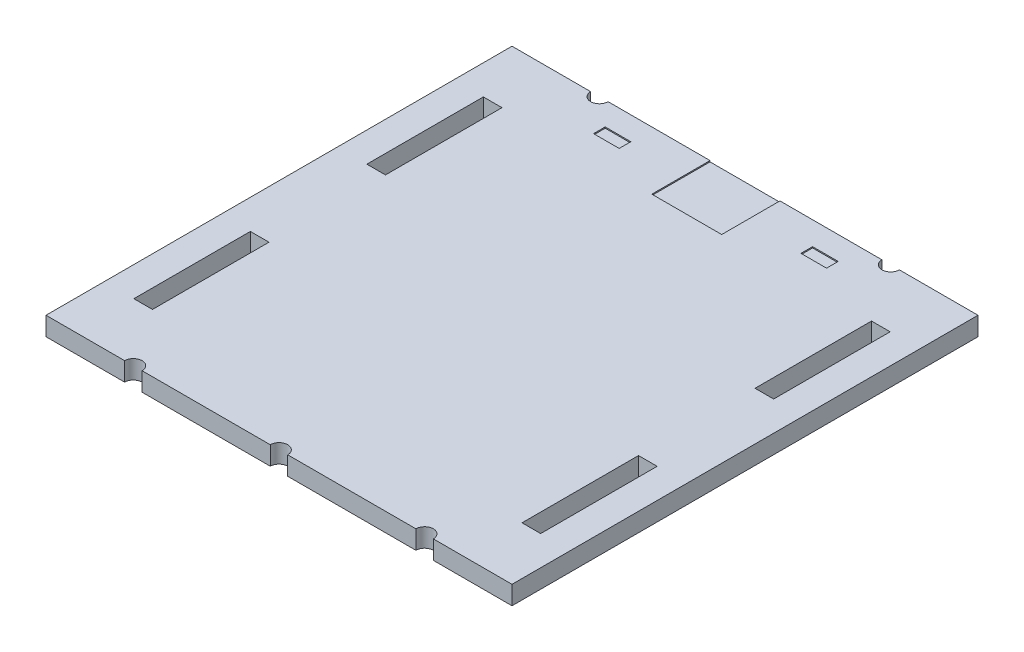
SolidWorks part; units mm, degrees
ref_plane "정면" through (0, 0, 0) normal (0, 0, 1) x (1, 0, 0)
ref_plane "윗면" through (0, 0, 0) normal (0, 1, 0) x (1, 0, 0)
ref_plane "우측면" through (0, 0, 0) normal (1, 0, 0) x (0, 0, -1)
sketch "스케치1" plane through (0, 0, 0) normal (0, 1, 0) x (1, 0, 0)
  line L1 (0, 0) -> (40, 0)
  line L2 (0, 0) -> (0, 40)
  line L3 (0, 40) -> (40, 40)
  line L4 (40, 0) -> (40, 40)
  dimension "D1" = 40
  dimension "D2" = 40
extrude "보스-돌출1" add sketch "스케치1" along normal blind 1.6
sketch "스케치2" plane through (0, 1.6, 0) normal (0, 1, 0) x (1, 0, 0)
  line L0 (0, 0) -> (40, 0) construction
  line L1 (40, 40) -> (0, 40) construction
  line L2 (0, 40) -> (0, 0) construction
  line L3 (40, 0) -> (40, 40) construction
  point P0 (7.5, 0)
  point P1 (20, 0)
  point P4 (32.5, 0)
  point P5 (32.5, 40)
  point P6 (20, 40)
  point P9 (7.5, 40)
  dimension "D1" = 7.5
  dimension "D2" = 7.5
hole_wizard "Ø1.5 (1.5) 지름 구멍1" positions "스케치5" profile "스케치6" hole size "Ø1.5" standard "ISO" end condition through all
sketch "스케치5" plane through (0, 1.6, 0) normal (0, 1, 0) x (1, 0, 0)
  point P0 (7.5, 0)
  point P3 (7.5, 40)
  point P6 (20, 0)
  point P9 (32.5, 0)
  point P12 (32.5, 40)
sketch "스케치6" plane through (7.5, 1.6, 0) normal (1, 0, 0) x (0, 0, 1)
  line L0 (0, 0) -> (0, 1.6)
  line L1 (0, 1.6) -> (0.75, 1.6)
  line L2 (0.75, 1.6) -> (0.75, 0)
  line L5 (0.75, 0) -> (0, 0)
  line L11 (0, -6.35) -> (0, 107.95) construction
  dimension "관통 구멍 지름" = 1.5
  dimension "관통 구멍 깊이" = 1.6
sketch "스케치8" plane through (0, 1.6, 0) normal (0, 1, 0) x (1, 0, 0)
  line L0 (0, 0) -> (6.75, 0) construction
  line L1 (2.54, 5) -> (4.14, 5)
  line L2 (2.54, 5) -> (2.54, 15)
  line L3 (2.54, 15) -> (4.14, 15)
  line L4 (4.14, 5) -> (4.14, 15)
  line L5 (2.54, 35) -> (4.14, 35)
  line L6 (2.54, 35) -> (2.54, 25)
  line L7 (2.54, 25) -> (4.14, 25)
  line L8 (4.14, 35) -> (4.14, 25)
  line L9 (37.46, 5) -> (35.86, 5)
  line L10 (37.46, 5) -> (37.46, 15)
  line L11 (37.46, 15) -> (35.86, 15)
  line L12 (35.86, 5) -> (35.86, 15)
  line L13 (37.46, 35) -> (35.86, 35)
  line L14 (37.46, 35) -> (37.46, 25)
  line L15 (37.46, 25) -> (35.86, 25)
  line L16 (35.86, 35) -> (35.86, 25)
  line L17 (0, 40) -> (0, 0) construction
  line L19 (40, 40) -> (33.25, 40) construction
  line L20 (40, 0) -> (40, 40) construction
  dimension "D3" = 5
  dimension "D4" = 2.54
  dimension "D1" = 10
  dimension "D2" = 1.6
  dimension "D5" = 5
  dimension "D6" = 2.54
extrude "컷-돌출2" cut sketch "스케치8" against normal through all
sketch "스케치9" plane through (0, 1.6, 0) normal (0, 1, 0) x (1, 0, 0)
  line L0 (31.75, 40) -> (8.25, 40) construction
  line L1 (10, 38) -> (12.2, 38)
  line L2 (10, 38) -> (10, 37)
  line L3 (10, 37) -> (12.2, 37)
  line L4 (12.2, 38) -> (12.2, 37)
  line L5 (27.8, 38) -> (30, 38)
  line L6 (27.8, 38) -> (27.8, 37)
  line L7 (27.8, 37) -> (30, 37)
  line L8 (30, 38) -> (30, 37)
  line L9 (17, 40) -> (23, 40)
  line L10 (17, 40) -> (17, 35)
  line L11 (17, 35) -> (23, 35)
  line L12 (23, 40) -> (23, 35)
  line L13 (0, 40) -> (0, 0) construction
  line L14 (40, 0) -> (40, 40) construction
  dimension "D1" = 10
  dimension "D2" = 10
  dimension "D3" = 2
  dimension "D4" = 1
  dimension "D5" = 2.2
  dimension "D6" = 6
  dimension "D7" = 17
  dimension "D8" = 5
sketch "스케치10" plane through (0, 0, 0) normal (0, -1, 0) x (1, 0, 0)
  line L0 (10, -38) -> (12.2, -38) construction
  line L1 (27.8, -37) -> (30, -37) construction
  line L2 (30, -38) -> (30, -37) construction
  line L3 (27.8, -38) -> (30, -38) construction
  line L4 (27.8, -38) -> (27.8, -37) construction
  line L5 (12.2, -38) -> (12.2, -37) construction
  line L6 (10, -37) -> (12.2, -37) construction
  line L7 (10, -38) -> (10, -37) construction
  line L8 (10, -38) -> (12.2, -38)
  line L9 (27.8, -37) -> (30, -37)
  line L10 (30, -38) -> (30, -37)
  line L11 (27.8, -38) -> (30, -38)
  line L12 (27.8, -38) -> (27.8, -37)
  line L13 (12.2, -38) -> (12.2, -37)
  line L14 (10, -37) -> (12.2, -37)
  line L15 (10, -38) -> (10, -37)
extrude "컷-돌출3" cut sketch "스케치9" against normal blind 0.1
extrude "컷-돌출4" cut sketch "스케치10" against normal blind 0.1
sketch "스케치11" plane through (0, 0, 0) normal (0, -1, 0) x (1, 0, 0)
  line L0 (12.03, -3) -> (12.73, -3)
  line L1 (12.03, -3) -> (12.03, -4.5)
  line L2 (12.03, -4.5) -> (12.73, -4.5)
  line L3 (12.73, -3) -> (12.73, -4.5)
  line L4 (13.3, -3) -> (14, -3)
  line L5 (13.3, -3) -> (13.3, -4.5)
  line L6 (13.3, -4.5) -> (14, -4.5)
  line L7 (14, -3) -> (14, -4.5)
  line L8 (14.57, -3) -> (15.27, -3)
  line L9 (14.57, -3) -> (14.57, -4.5)
  line L10 (14.57, -4.5) -> (15.27, -4.5)
  line L11 (15.27, -3) -> (15.27, -4.5)
  line L12 (15.84, -3) -> (16.54, -3)
  line L13 (15.84, -3) -> (15.84, -4.5)
  line L14 (15.84, -4.5) -> (16.54, -4.5)
  line L15 (16.54, -3) -> (16.54, -4.5)
  line L16 (17.11, -3) -> (17.81, -3)
  line L17 (17.11, -3) -> (17.11, -4.5)
  line L18 (17.11, -4.5) -> (17.81, -4.5)
  line L19 (17.81, -3) -> (17.81, -4.5)
  line L20 (18.38, -3) -> (19.08, -3)
  line L21 (18.38, -3) -> (18.38, -4.5)
  line L22 (18.38, -4.5) -> (19.08, -4.5)
  line L23 (19.08, -3) -> (19.08, -4.5)
  line L24 (19.65, -3) -> (20.35, -3)
  line L25 (19.65, -3) -> (19.65, -4.5)
  line L26 (19.65, -4.5) -> (20.35, -4.5)
  line L27 (20.35, -3) -> (20.35, -4.5)
  line L28 (20.92, -3) -> (21.62, -3)
  line L29 (20.92, -3) -> (20.92, -4.5)
  line L30 (20.92, -4.5) -> (21.62, -4.5)
  line L31 (21.62, -3) -> (21.62, -4.5)
  line L32 (22.19, -3) -> (22.89, -3)
  line L33 (22.19, -3) -> (22.19, -4.5)
  line L34 (22.19, -4.5) -> (22.89, -4.5)
  line L35 (22.89, -3) -> (22.89, -4.5)
  line L36 (23.46, -3) -> (24.16, -3)
  line L37 (23.46, -3) -> (23.46, -4.5)
  line L38 (23.46, -4.5) -> (24.16, -4.5)
  line L39 (24.16, -3) -> (24.16, -4.5)
  line L40 (24.73, -3) -> (25.43, -3)
  line L41 (24.73, -3) -> (24.73, -4.5)
  line L42 (24.73, -4.5) -> (25.43, -4.5)
  line L43 (25.43, -3) -> (25.43, -4.5)
  line L44 (26, -3) -> (26.7, -3)
  line L45 (26, -3) -> (26, -4.5)
  line L46 (26, -4.5) -> (26.7, -4.5)
  line L47 (26.7, -3) -> (26.7, -4.5)
  line L48 (27.27, -3) -> (27.97, -3)
  line L49 (27.27, -3) -> (27.27, -4.5)
  line L50 (27.27, -4.5) -> (27.97, -4.5)
  line L51 (27.97, -3) -> (27.97, -4.5)
  line L54 (0, -40) -> (0, 0) construction
  line L55 (8.25, 0) -> (19.25, 0) construction
  dimension "D1" = 1.5
  dimension "D2" = 0.7
  dimension "D5" = 12.03
  dimension "D4" = 3
  dimension "D3" = 13
extrude "컷-돌출5" cut sketch "스케치11" against normal blind 0.1
sketch "스케치12" plane through (0, 1.6, 0) normal (0, 1, 0) x (1, 0, 0)
  line L0 (0, 40) -> (0, 0) construction
  line L1 (12.5, 16) -> (25.5, 16)
  line L2 (12.5, 16) -> (12.5, 29)
  line L3 (12.5, 29) -> (25.5, 29)
  line L4 (25.5, 16) -> (25.5, 29)
  line L5 (0, 0) -> (6.75, 0) construction
  dimension "D1" = 12.5
  dimension "D2" = 16
  dimension "D3" = 13
  dimension "D4" = 13
equation "\"D5@스케치8\"=\"D3@스케치8\""
equation "\"D6@스케치8\"=\"D4@스케치8\""
equation "\"D2@스케치2\"=\"D1@스케치2\""
equation "\"D2@스케치9\"=\"D1@스케치9\""
equation "\"D7@스케치9\"=(40-\"D6@스케치9\")/2"
equation "\"D5@스케치11\"=(40-(1.27*12+0.7))/2"
